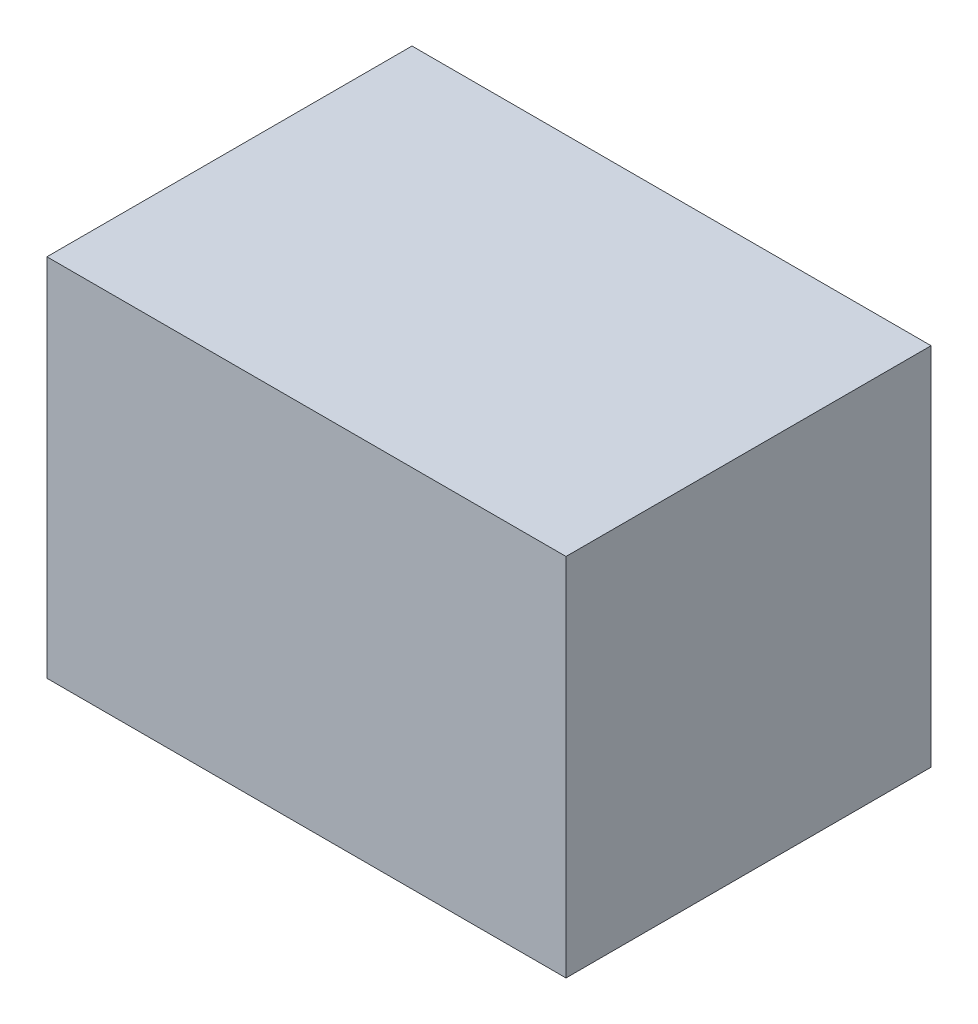
SolidWorks part; units mm, degrees
ref_plane "Front Plane" through (0, 0, 0) normal (0, 0, 1) x (1, 0, 0)
ref_plane "Top Plane" through (0, 0, 0) normal (0, 1, 0) x (1, 0, 0)
ref_plane "Right Plane" through (0, 0, 0) normal (1, 0, 0) x (0, 0, -1)
sketch "Sketch3" plane through (0, 0, 0) normal (0, 1, 0) x (1, 0, 0)
  line L1 (0, 0) -> (91, 0)
  line L2 (0, 0) -> (0, 64)
  line L3 (0, 64) -> (91, 64)
  line L4 (91, 0) -> (91, 64)
  line L5 (0, 0) -> (72, 0)
  line L6 (0, 0) -> (0, 64)
  line L7 (0, 64) -> (72, 64)
  line L8 (72, 0) -> (72, 64)
  dimension "D1" = 91
  dimension "D2" = 64
  dimension "D3" = 72
  dimension "D4" = 64
extrude "Boss-Extrude1" add sketch "Sketch3" along normal blind 64 contours L8 L1 L4 L3 | L1 L8 L3 L2
